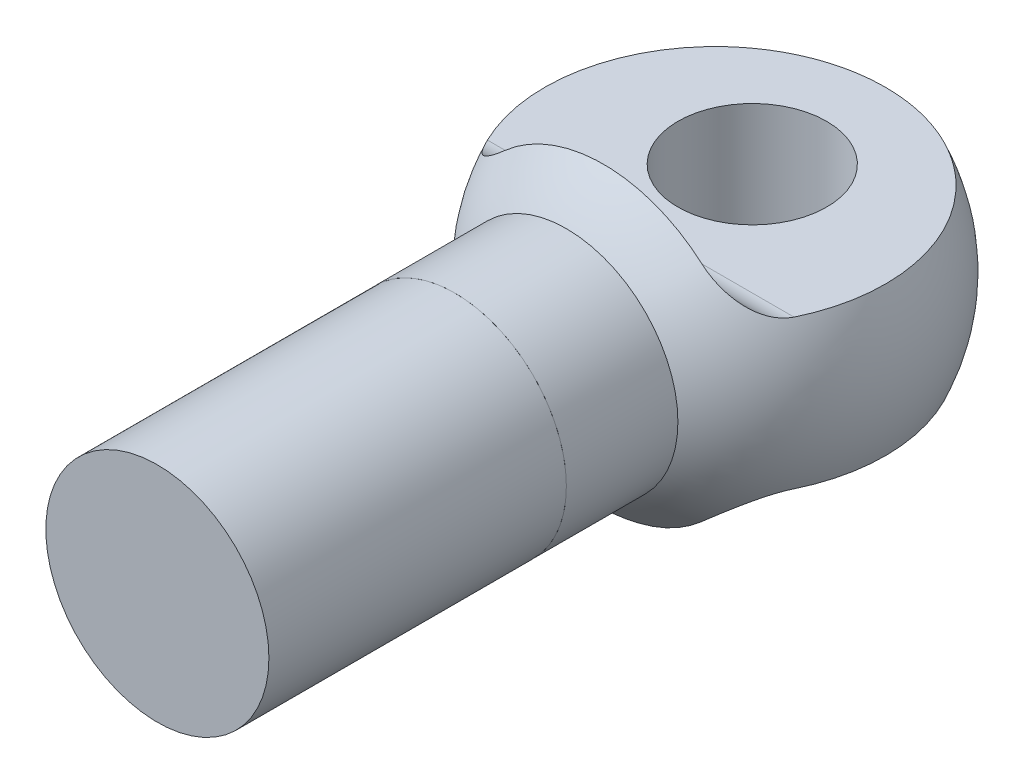
SolidWorks part; units mm, degrees
ref_plane "Alzado" through (0, 0, 0) normal (0, 0, 1) x (1, 0, 0)
ref_plane "Planta" through (0, 0, 0) normal (0, 1, 0) x (1, 0, 0)
ref_plane "Vista lateral" through (0, 0, 0) normal (1, 0, 0) x (0, 0, -1)
sketch "Croquis1" plane through (0, 0, 0) normal (0, 0, 1) x (1, 0, 0)
  circle A0 centre (0, 0) radius 3
  dimension "D1" = 6
extrude "Saliente-Extruir3" add sketch "Croquis1" along normal blind 8
cosmetic thread "Rosca cosmética1" parameters "D2"=4.891
cosmetic thread "Rosca cosmética2" parameters "D2"=4.891
sketch "Croquis4" plane through (0, 0, 0) normal (0, 0, -1) x (-1, 0, 0)
  circle A0 centre (0, 0) radius 3
  dimension "D1" = 6
extrude "Saliente-Extruir5" add sketch "Croquis4" along normal blind 3 separate body
sketch "Croquis5" plane through (0, 0, 0) normal (0, 1, 0) x (1, 0, 0)
  line L0 (-3, 3) -> (0, 3)
  line L1 (-3, 3) -> (-3, 0) construction
  line L2 (0, 0) -> (0, 50000) construction
  line L5 (0, 12) -> (0, 3)
  arc A0 (0, 12) -> (-3, 3) centre (0, 7) ccw
  dimension "D1" = 5
revolve "Revolución1" add sketch "Croquis5" angle 360 about L2
sketch "Croquis7" plane through (0, 0, 0) normal (1, 0, 0) x (0, 0, -1)
  line L0 (0, 0) -> (50000, 0) construction
  line L1 (4, 5) -> (12, 5)
  line L2 (4, 5) -> (4, 2)
  line L3 (4, 2) -> (12, 2)
  line L4 (12, 5) -> (12, 2)
  line L5 (3, 3) -> (3, -3) construction
  dimension "D1" = 2
  dimension "D2" = 3
  dimension "D3" = 1
  dimension "D4" = 8
extrude "Cortar-Extruir3" cut sketch "Croquis7" against normal through all and the other way through all
fillet "Redondeo2" radius 1 1 edges at (0, 2, -4)
mirror "Simetría2" about plane through (0, 0, 0) normal (0, 1, 0) of "Redondeo2", "Cortar-Extruir3"
sketch "Croquis8" plane through (0, 0, 0) normal (0, 1, 0) x (1, 0, 0)
  line L0 (2.6458, 4) -> (-2.6458, 4) construction
  line L1 (0, 0) -> (0, 50000) construction
  line L2 (-3, 3) -> (-3, 0) construction
  circle A0 centre (0, 8) radius 2
  dimension "D1" = 4
  dimension "D2" = 4
  dimension "D3" = 3
extrude "Cortar-Extruir4" cut sketch "Croquis8" against normal through all and the other way through all
